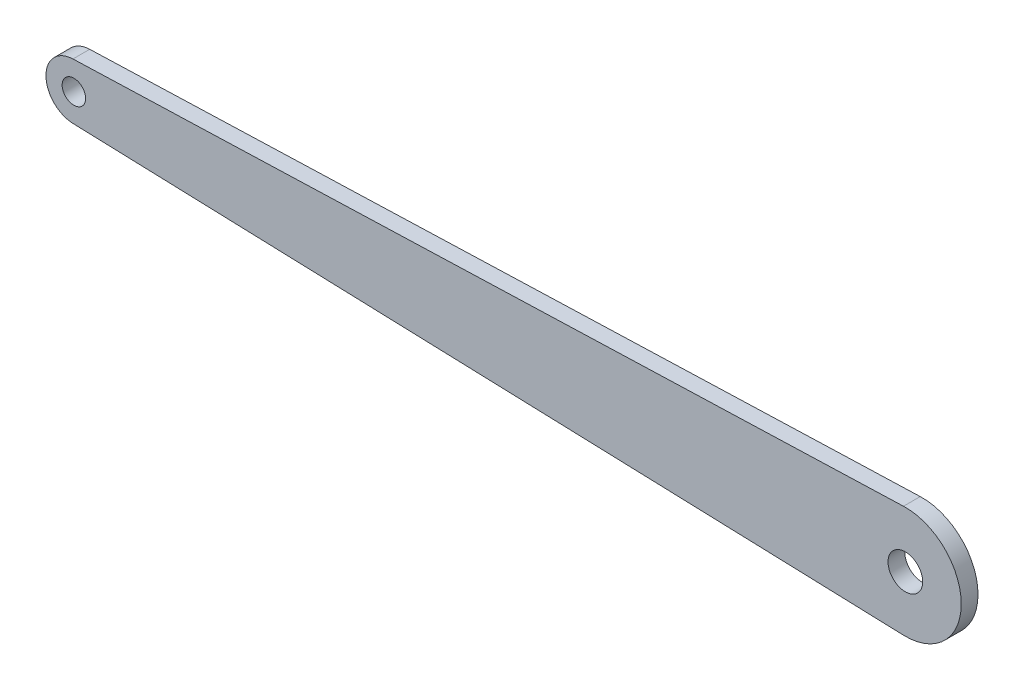
SolidWorks part; units mm, degrees
ref_plane "前视基准面" through (0, 0, 0) normal (0, 0, 1) x (1, 0, 0)
ref_plane "上视基准面" through (0, 0, 0) normal (0, 1, 0) x (1, 0, 0)
ref_plane "右视基准面" through (0, 0, 0) normal (1, 0, 0) x (0, 0, -1)
other "Configuration Table"
sketch "草图1" plane through (0, 0, -59.1117) normal (0, 0, -1) x (-1, 0, 0)
  line L0 (82.2377, 117.7962) -> (231.0577, 117.7962) construction
  line L1 (231.2257, 122.7934) -> (82.5737, 127.7906)
  line L2 (82.5737, 107.8019) -> (231.2257, 112.799)
  arc A0 (82.5737, 127.7906) -> (82.5737, 107.8019) centre (82.2377, 117.7962) ccw
  circle A1 centre (82.2377, 117.7962) radius 3.1
  circle A2 centre (231.0577, 117.7962) radius 2.1
  arc A3 (231.2257, 112.799) -> (231.2257, 122.7934) centre (231.0577, 117.7962) ccw
  dimension "D1" = 10
  dimension "D2" = 6.2
  dimension "D4" = 4.2
  dimension "D5" = 5
  dimension "D3" = 148.82
extrude "凸台-拉伸1" add sketch "草图1" along normal blind 3
